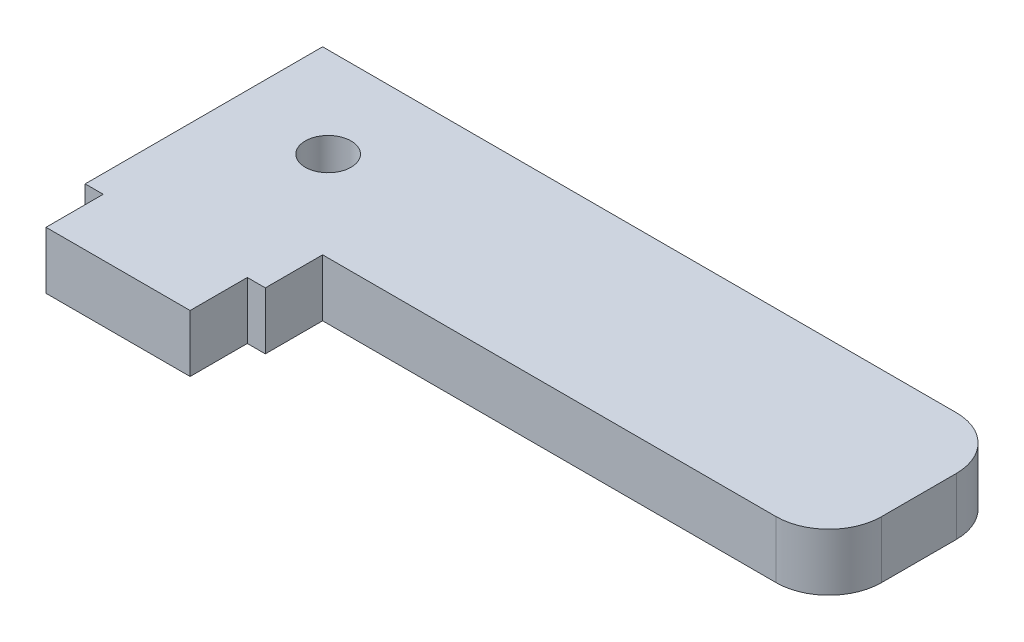
SolidWorks part; units mm, degrees
ref_plane "Front Plane" through (0, 0, 0) normal (0, 0, 1) x (1, 0, 0)
ref_plane "Top Plane" through (0, 0, 0) normal (0, 1, 0) x (1, 0, 0)
ref_plane "Right Plane" through (0, 0, 0) normal (1, 0, 0) x (0, 0, -1)
sketch "Sketch1" plane through (0, 0, 0) normal (0, 1, 0) x (1, 0, 0)
  line L0 (0, 0) -> (0, 16.355)
  line L1 (0, 16.355) -> (38.1, 16.355)
  line L2 (38.1, 16.355) -> (38.1, 6.355)
  line L3 (38.1, 6.355) -> (10, 6.355)
  line L4 (10, 6.355) -> (10, 0)
  line L5 (10, 0) -> (0, 0)
  circle A0 centre (5.313, 11.35) radius 1.27
  point P9 (5.7067, 12.3563)
  point P10 (5.313, 11.35)
  dimension "D5" = 2.54
  dimension "D7" = 5.313
  dimension "D1" = 16.355
  dimension "D2" = 38.1
  dimension "D3" = 10
  dimension "D4" = 10
  dimension "D6" = 5.005
extrude "Boss-Extrude1" add sketch "Sketch1" along normal blind 3.175
fillet "Fillet1" radius 2.921 2 edges at (38.1, 1.5875, -6.355) (38.1, 1.5875, -16.355)
sketch "Sketch2" plane through (0, 3.175, 0) normal (0, 1, 0) x (1, 0, 0)
  line L0 (0, 0) -> (10, 0) construction
  line L1 (10, 3.175) -> (9, 3.175)
  line L2 (10, 3.175) -> (10, 0)
  line L3 (10, 0) -> (9, 0)
  line L4 (9, 3.175) -> (9, 0)
  line L5 (10, 0) -> (10, 6.355) construction
  line L6 (0, 0) -> (1, 0)
  line L7 (0, 0) -> (0, 3.175)
  line L8 (0, 3.175) -> (1, 3.175)
  line L9 (1, 0) -> (1, 3.175)
  dimension "D1" = 1
  dimension "D2" = 3.175
extrude "Cut-Extrude1" cut sketch "Sketch2" against normal through all
